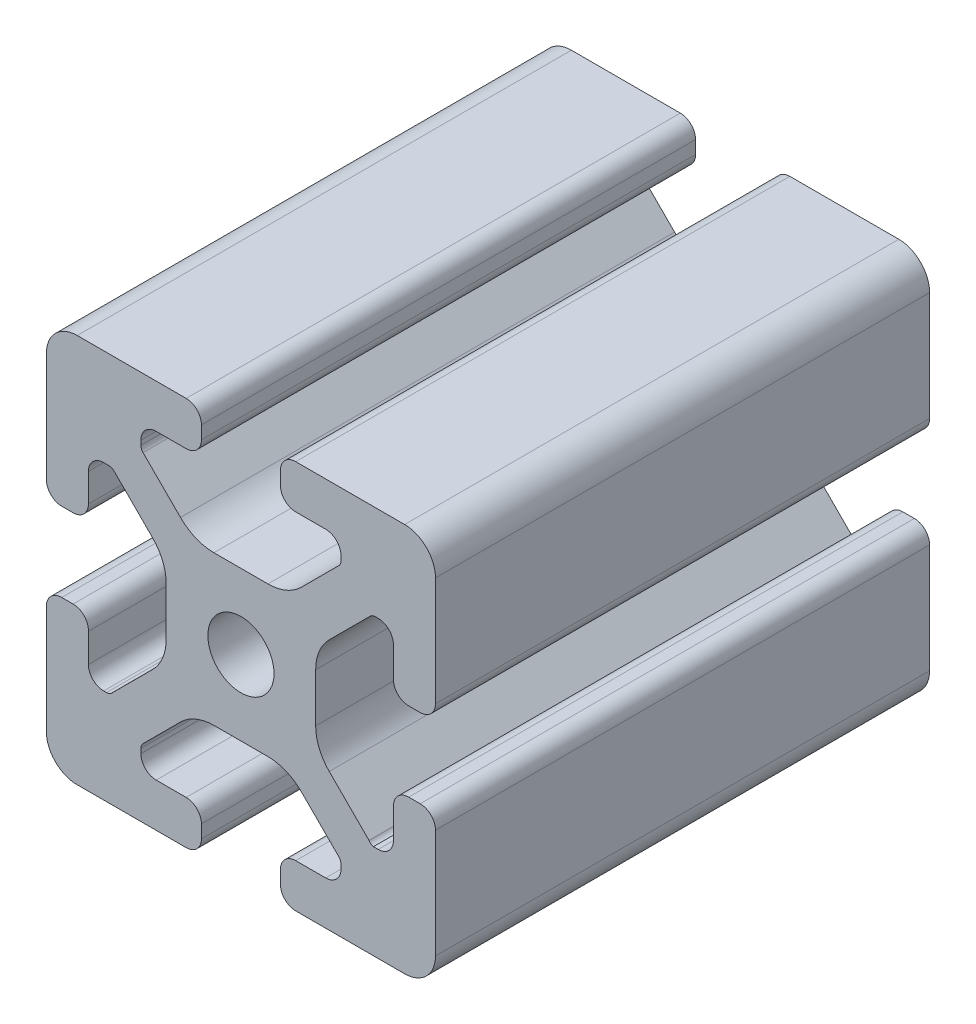
SolidWorks part; units mm, degrees
material "6061 Alloy"
ref_plane "Front Plane" through (0, 0, 0) normal (0, 0, 1) x (1, 0, 0)
ref_plane "Top Plane" through (0, 0, 0) normal (0, 1, 0) x (1, 0, 0)
ref_plane "Right Plane" through (0, 0, 0) normal (1, 0, 0) x (0, 0, -1)
sketch "Sketch1" plane through (0, 0, 0) normal (0, 0, 1) x (1, 0, 0)
  line L0 (0, 19.7407) -> (0, -19.7407) construction
  line L1 (19.0335, 0) -> (-20.7246, 0) construction
  line L2 (-8.715, -15.5246) -> (-5.63, -15.5246)
  line L3 (-10.285, -13.9546) -> (-10.285, -13.4925)
  line L4 (-6.2171, -9.1098) -> (-10.0624, -12.9551)
  line L5 (2.7773, -7.685) -> (-2.7773, -7.685)
  line L6 (10.0624, -12.9551) -> (6.2171, -9.1098)
  line L7 (10.285, -13.9546) -> (10.285, -13.4925)
  line L8 (5.63, -15.5246) -> (8.715, -15.5246)
  line L9 (4.06, -18.43) -> (4.06, -17.0946)
  line L10 (-4.06, -18.43) -> (-4.06, -17.0946)
  line L11 (15.68, -8.7154) -> (15.68, -5.63)
  line L12 (-14.11, -10.2854) -> (-13.8169, -10.2854)
  line L13 (20, -16.83) -> (20, -5.63)
  line L14 (20, 5.63) -> (20, 13.0011)
  line L15 (-16.83, 20) -> (-5.63, 20)
  line L16 (5.63, 20) -> (12.9796, 20)
  line L18 (-8.715, 15.5246) -> (-5.63, 15.5246)
  line L19 (-20, -17.0184) -> (-20, -5.7579)
  line L20 (-20, 5.573) -> (-20, 13.0045)
  line L21 (-15.68, -8.7154) -> (-15.68, -5.7579)
  line L23 (-16.6746, -20) -> (-5.63, -20)
  line L24 (5.63, -20) -> (13, -20)
  line L53 (14.11, -10.2854) -> (13.6201, -10.2854)
  line L54 (13.1637, -9.947) -> (9.0762, -5.8595)
  line L55 (7.685, -2.5008) -> (7.685, 2.5008)
  line L56 (9.0762, 5.8595) -> (13.2795, 10.0628)
  line L57 (13.8169, 10.2854) -> (14.11, 10.2854)
  line L58 (15.68, 8.7154) -> (15.68, 5.63)
  line L59 (17.25, 4.06) -> (18.43, 4.06)
  line L61 (20, 13.0011) -> (20, 16.83)
  line L62 (16.83, 20) -> (12.9796, 20)
  line L64 (4.06, 18.43) -> (4.06, 17.0946)
  line L65 (5.63, 15.5246) -> (8.715, 15.5246)
  line L66 (10.285, 13.9546) -> (10.285, 13.4925)
  line L67 (10.0624, 12.9551) -> (6.2171, 9.1098)
  line L68 (2.7773, 7.685) -> (-2.7773, 7.685)
  line L69 (-6.2171, 9.1098) -> (-10.0624, 12.9551)
  line L70 (-10.285, 13.4925) -> (-10.285, 13.9546)
  line L72 (-4.06, 17.0946) -> (-4.06, 18.43)
  line L75 (-20, 16.83) -> (-20, 13.0045)
  line L77 (-18.43, 4.003) -> (-17.25, 4.003)
  line L78 (-15.68, 5.573) -> (-15.68, 8.4757)
  line L79 (-14.0552, 10.0447) -> (-13.7199, 10.033)
  line L80 (-13.0405, 9.8238) -> (-9.0762, 5.8595)
  line L81 (-7.685, 2.5008) -> (-7.685, -2.5008)
  line L82 (-9.0762, -5.8595) -> (-13.2795, -10.0628)
  line L85 (-17.25, -4.1204) -> (-18.43, -4.1204)
  line L100 (13, -20) -> (16.83, -20)
  line L103 (18.43, -4.06) -> (17.25, -4.06)
  arc A0 (-5.63, -15.5246) -> (-4.06, -17.0946) centre (-5.63, -17.0946) cw
  arc A1 (-8.715, -15.5246) -> (-10.285, -13.9546) centre (-8.715, -13.9546) cw
  arc A2 (-10.285, -13.4925) -> (-10.0624, -12.9551) centre (-9.525, -13.4925) cw
  arc A3 (-6.2171, -9.1098) -> (-2.7773, -7.685) centre (-2.7773, -12.5496) cw
  arc A4 (2.7773, -7.685) -> (6.2171, -9.1098) centre (2.7773, -12.5496) cw
  arc A5 (10.0624, -12.9551) -> (10.285, -13.4925) centre (9.525, -13.4925) cw
  arc A6 (10.285, -13.9546) -> (8.715, -15.5246) centre (8.715, -13.9546) cw
  arc A7 (4.06, -17.0946) -> (5.63, -15.5246) centre (5.63, -17.0946) cw
  arc A8 (5.63, -20) -> (4.06, -18.43) centre (5.63, -18.43) cw
  arc A9 (-4.06, -18.43) -> (-5.63, -20) centre (-5.63, -18.43) cw
  circle A45 centre (0, 0) radius 3.4
  arc A46 (17.25, -4.06) -> (15.68, -5.63) centre (17.25, -5.63) ccw
  arc A47 (14.11, -10.2854) -> (15.68, -8.7154) centre (14.11, -8.7154) ccw
  arc A48 (13.1637, -9.947) -> (13.6201, -10.2854) centre (13.8117, -9.55) ccw
  arc A49 (7.685, -2.5008) -> (9.0762, -5.8595) centre (12.435, -2.5008) ccw
  arc A50 (9.0762, 5.8595) -> (7.685, 2.5008) centre (12.435, 2.5008) ccw
  arc A51 (13.8169, 10.2854) -> (13.2795, 10.0628) centre (13.8169, 9.5254) ccw
  arc A52 (15.68, 8.7154) -> (14.11, 10.2854) centre (14.11, 8.7154) ccw
  arc A53 (15.68, 5.63) -> (17.25, 4.06) centre (17.25, 5.63) ccw
  arc A54 (18.43, 4.06) -> (20, 5.63) centre (18.43, 5.63) ccw
  arc A55 (20, 16.83) -> (16.83, 20) centre (16.83, 16.83) ccw
  arc A56 (5.63, 20) -> (4.06, 18.43) centre (5.63, 18.43) ccw
  arc A57 (4.06, 17.0946) -> (5.63, 15.5246) centre (5.63, 17.0946) ccw
  arc A58 (10.285, 13.9546) -> (8.715, 15.5246) centre (8.715, 13.9546) ccw
  arc A59 (10.0624, 12.9551) -> (10.285, 13.4925) centre (9.525, 13.4925) ccw
  arc A60 (2.7773, 7.685) -> (6.2171, 9.1098) centre (2.7773, 12.5496) ccw
  arc A61 (-6.2171, 9.1098) -> (-2.7773, 7.685) centre (-2.7773, 12.5496) ccw
  arc A62 (-10.285, 13.4925) -> (-10.0624, 12.9551) centre (-9.525, 13.4925) ccw
  arc A63 (-8.715, 15.5246) -> (-10.285, 13.9546) centre (-8.715, 13.9546) ccw
  arc A64 (-5.63, 15.5246) -> (-4.06, 17.0946) centre (-5.63, 17.0946) ccw
  arc A65 (-4.06, 18.43) -> (-5.63, 20) centre (-5.63, 18.43) ccw
  arc A66 (-16.83, 20) -> (-20, 16.83) centre (-16.83, 16.83) ccw
  arc A67 (-20, 5.573) -> (-18.43, 4.003) centre (-18.43, 5.573) ccw
  arc A68 (-17.25, 4.003) -> (-15.68, 5.573) centre (-17.25, 5.573) ccw
  arc A69 (-14.0552, 10.0447) -> (-15.68, 8.4757) centre (-14.11, 8.4757) ccw
  arc A70 (-13.0405, 9.8238) -> (-13.7199, 10.033) centre (-13.5779, 9.2864) ccw
  arc A71 (-7.685, 2.5008) -> (-9.0762, 5.8595) centre (-12.435, 2.5008) ccw
  arc A72 (-9.0762, -5.8595) -> (-7.685, -2.5008) centre (-12.435, -2.5008) ccw
  arc A73 (-13.8169, -10.2854) -> (-13.2795, -10.0628) centre (-13.8169, -9.5254) ccw
  arc A74 (-15.68, -8.7154) -> (-14.11, -10.2854) centre (-14.11, -8.7154) ccw
  arc A75 (-15.68, -5.7579) -> (-17.25, -4.1204) centre (-17.2485, -5.6904) ccw
  arc A76 (-18.43, -4.1204) -> (-20, -5.7579) centre (-18.4315, -5.6904) ccw
  arc A77 (-20, -17.0184) -> (-16.6746, -20) centre (-16.8354, -16.8341) ccw
  arc A88 (16.83, -20) -> (20, -16.83) centre (16.83, -16.83) ccw
  arc A89 (20, -5.63) -> (18.43, -4.06) centre (18.43, -5.63) ccw
  dimension "D2" = 6.8
  dimension "D7" = 20.57
  dimension "D1" = 40
  dimension "D3" = 4.32
  dimension "D4" = 15.37
  dimension "D5" = 20
  dimension "D6" = 4.32
  dimension "D9" = 15.37
extrude "Extrude1" add sketch "Sketch1" against normal blind 50.8
sketch "Sketch2" plane through (0, -20, 0) normal (0, -1, 0) x (1, 0, 0)
  circle A0 centre (0, -15.6) radius 1.5
  circle A1 centre (0, -35.2) radius 1.5
  dimension "D1" = 3
hole_wizard "Ø8.0mm Dowel Hole1" positions "Sketch4" profile "Sketch5" hole size "Ø8.0" standard "ANSI Metric" end condition through all
sketch "Sketch4" plane through (0, -20, 0) normal (0, -1, 0) x (-1, 0, 0)
  point P0 (0, 15.6)
  point P3 (0, 35.2)
sketch "Sketch5" plane through (0, -20, -15.6) normal (1, 0, 0) x (0, 0, -1)
  line L0 (0, 0) -> (0, 40)
  line L1 (0, 40) -> (4, 40)
  line L2 (4, 40) -> (4, 0)
  line L5 (4, 0) -> (0, 0)
  line L11 (0, -6.35) -> (0, 107.95) construction
  dimension "Thru Hole Dia." = 8
  dimension "Thru Hole Depth" = 40
